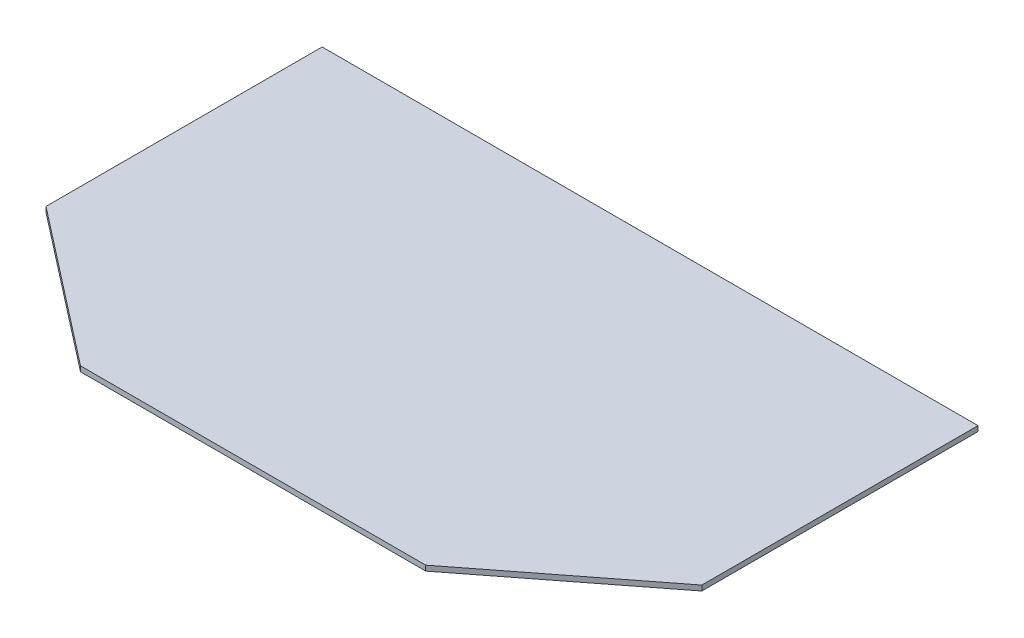
SolidWorks part; units mm, degrees
ref_plane "Front Plane" through (0, 0, 0) normal (0, 0, 1) x (1, 0, 0)
ref_plane "Top Plane" through (0, 0, 0) normal (0, 1, 0) x (1, 0, 0)
ref_plane "Right Plane" through (0, 0, 0) normal (1, 0, 0) x (0, 0, -1)
sketch "Sketch1" plane through (0, 0, 0) normal (0, 1, 0) x (1, 0, 0)
  line L0 (-190, 80) -> (190, 80)
  line L2 (190, 80) -> (190, 60)
  line L3 (-190, 60) -> (-190, -60)
  line L4 (190, 60) -> (190, -60)
  line L6 (190, -60) -> (190, -80)
  line L7 (190, -80) -> (100, -150)
  line L8 (100, -150) -> (-100, -150)
  line L9 (-100, -150) -> (-190, -80)
  line L10 (-190, -80) -> (-190, -60)
  line L14 (-190, 60) -> (-190, 80)
  dimension "D5" = 20
  dimension "D6" = 20
  dimension "D10" = 20
  dimension "D12" = 20
  dimension "D19" = 90
extrude "Boss-Extrude1" add sketch "Sketch1" along normal blind 3
